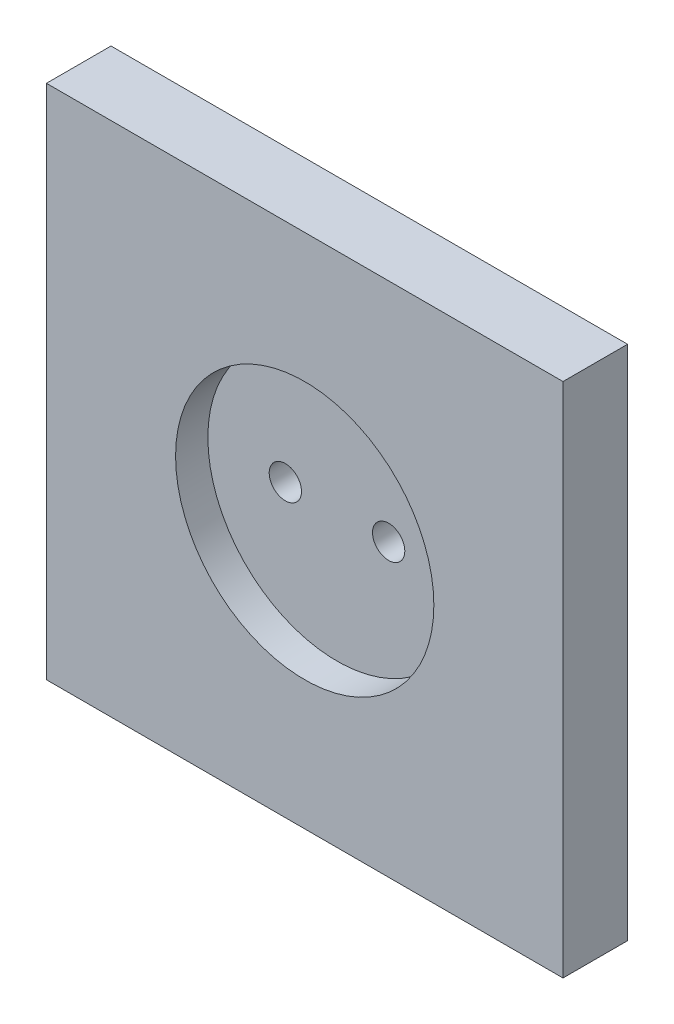
SolidWorks part; units mm, degrees
ref_plane "Спереди" through (0, 0, 0) normal (0, 0, 1) x (1, 0, 0)
ref_plane "Сверху" through (0, 0, 0) normal (0, 1, 0) x (1, 0, 0)
ref_plane "Справа" through (0, 0, 0) normal (1, 0, 0) x (0, 0, -1)
other "Configuration Table"
sketch "Эскиз1" plane through (0, 0, 0) normal (0, 0, 1) x (1, 0, 0)
  line L1 (0, 0) -> (80, 0)
  line L2 (0, 0) -> (0, 80)
  line L3 (0, 80) -> (80, 80)
  line L4 (80, 0) -> (80, 80)
  dimension "D1" = 80
extrude "Бобышка-Вытянуть1" add sketch "Эскиз1" along normal blind 10
sketch "Эскиз2" plane through (0, 0, 10) normal (0, 0, 1) x (1, 0, 0)
  line L0 (0, 40) -> (40, 40) construction
  line L1 (0, 80) -> (0, 0) construction
  line L2 (40, 40) -> (40, 80) construction
  line L3 (80, 80) -> (0, 80) construction
  circle A0 centre (40, 40) radius 20
  dimension "D1" = 40
extrude "Вырез-Вытянуть1" cut sketch "Эскиз2" against normal blind 5
sketch "Эскиз3" plane through (0, 0, 5) normal (0, 0, 1) x (1, 0, 0)
  line L0 (40, 40) -> (32, 40) construction
  line L1 (40, 40) -> (48, 40) construction
  circle A0 centre (32, 40) radius 2.5
  circle A1 centre (48, 40) radius 2.5
  dimension "D1" = 5
  dimension "D2" = 8
extrude "Вырез-Вытянуть2" cut sketch "Эскиз3" against normal blind 5
